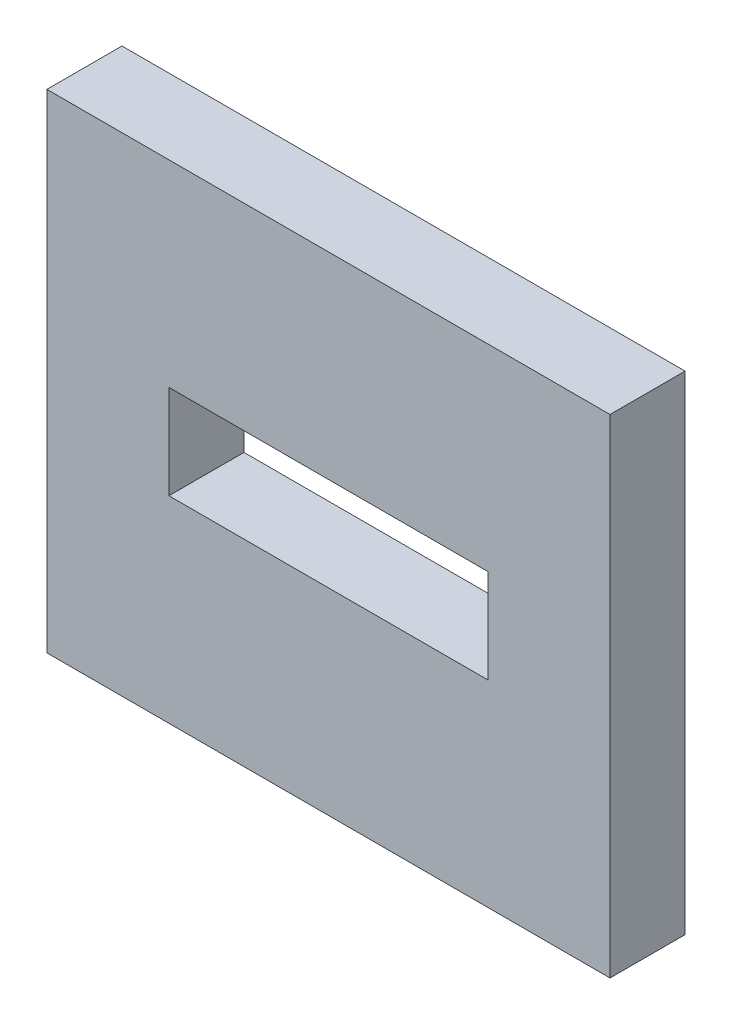
SolidWorks part; units mm, degrees
ref_plane "Front" through (0, 0, 0) normal (0, 0, 1) x (1, 0, 0)
ref_plane "Top" through (0, 0, 0) normal (0, 1, 0) x (1, 0, 0)
ref_plane "Right" through (0, 0, 0) normal (1, 0, 0) x (0, 0, -1)
sketch "Sketch1" plane through (0, 0, 0) normal (0, 0, 1) x (1, 0, 0)
  line L1 (-7.5, -3.5476) -> (7.5, -3.5476)
  line L2 (-7.5, -3.5476) -> (-7.5, 9.4524)
  line L3 (-7.5, 9.4524) -> (7.5, 9.4524)
  line L4 (7.5, -3.5476) -> (7.5, 9.4524)
  line L5 (-4.25, 1.7024) -> (4.25, 1.7024)
  line L6 (-4.25, 1.7024) -> (-4.25, 4.2024)
  line L7 (-4.25, 4.2024) -> (4.25, 4.2024)
  line L8 (4.25, 1.7024) -> (4.25, 4.2024)
  point P8 (0, 1.7024)
  point P9 (0, -3.5476)
  point P10 (1.974, 3.3117)
  point P12 (-7.5, 2.9524)
  point P13 (-4.25, 2.9524)
  point P14 (-7.5, 11.6068)
  dimension "D1" = 2.5
  dimension "D2" = 13
  dimension "D3" = 15
  dimension "D4" = 8.5
extrude "Boss-Extrude1" add sketch "Sketch1" along normal blind 2
